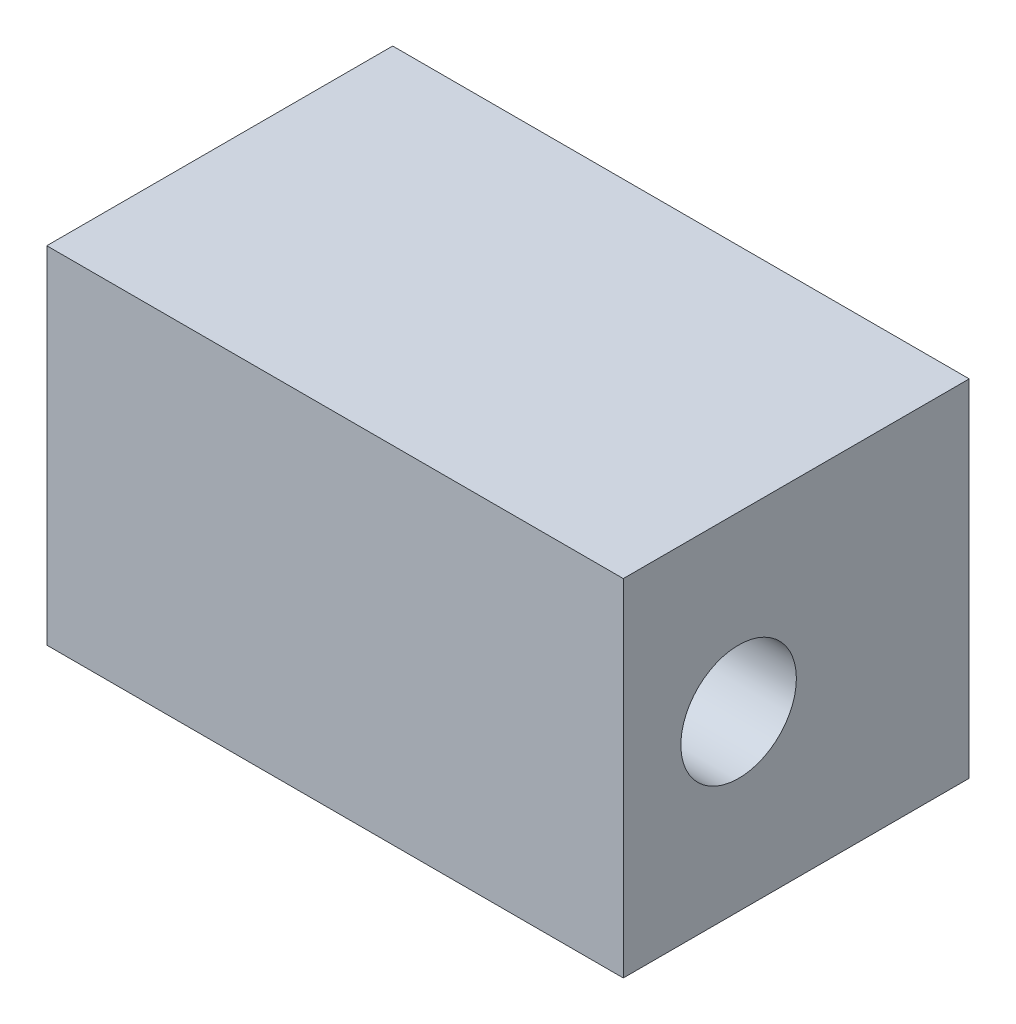
SolidWorks part; units mm, degrees
ref_plane "Front Plane" through (0, 0, 0) normal (0, 0, 1) x (1, 0, 0)
ref_plane "Top Plane" through (0, 0, 0) normal (0, 1, 0) x (1, 0, 0)
ref_plane "Right Plane" through (0, 0, 0) normal (1, 0, 0) x (0, 0, -1)
sketch "Sketch1" plane through (0, 0, 0) normal (1, 0, 0) x (0, 0, -1)
  line L1 (-24.1738, 18.7872) -> (13.9262, 18.7872)
  line L2 (-24.1738, 18.7872) -> (-24.1738, -19.3128)
  line L3 (-24.1738, -19.3128) -> (13.9262, -19.3128)
  line L4 (13.9262, 18.7872) -> (13.9262, -19.3128)
  dimension "D1" = 38.1
  dimension "D2" = 38.1
extrude "Boss-Extrude1" add sketch "Sketch1" against normal blind 63.5
sketch "Sketch2" plane through (0, 0, 0) normal (1, 0, 0) x (0, 0, -1)
  line L0 (13.9262, -19.3128) -> (13.9262, 18.7872) construction
  line L1 (13.9262, 18.7872) -> (-24.1738, 18.7872) construction
  circle A0 centre (-11.4738, -0.2628) radius 6.3627
  dimension "D1" = 12.7254
  dimension "D2" = 25.4
  dimension "D3" = 19.05
extrude "Cut-Extrude1" cut sketch "Sketch2" against normal blind 57.15
sketch "Sketch6" plane through (0, 0, -13.9262) normal (0, 0, -1) x (-1, 0, 0)
  line L0 (63.5, 18.7872) -> (0, 18.7872) construction
  line L1 (0, -19.3128) -> (0, 18.7872) construction
  circle A0 centre (25.4, -0.2628) radius 2.0193
  dimension "D1" = 4.0386
  dimension "D2" = 19.05
  dimension "D3" = 25.4
extrude "Cut-Extrude4" cut sketch "Sketch6" against normal blind 12.7
sketch "Sketch7" plane through (0, 0, -13.9262) normal (0, 0, -1) x (-1, 0, 0)
  line L0 (63.5, 18.7872) -> (0, 18.7872) construction
  line L1 (63.5, -19.3128) -> (63.5, 18.7872) construction
  circle A0 centre (50.8, -0.2628) radius 0.635
  dimension "D1" = 1.27
  dimension "D2" = 19.05
  dimension "D3" = 12.7
extrude "Cut-Extrude5" cut sketch "Sketch7" against normal blind 22.86
